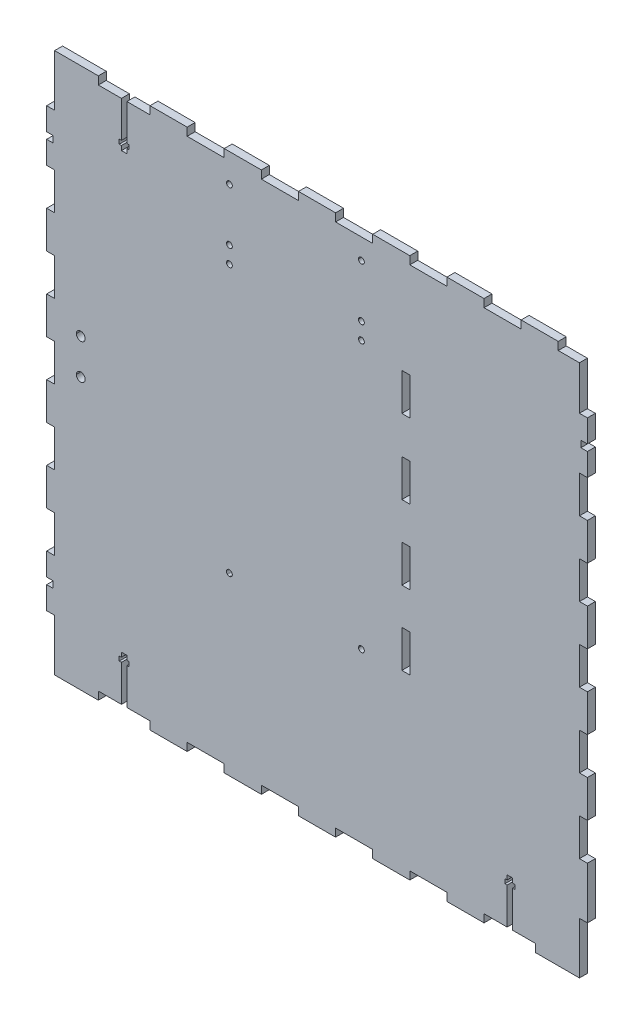
SolidWorks part; units mm, degrees
ref_plane "Front Plane" through (0, 0, 0) normal (0, 0, 1) x (1, 0, 0)
ref_plane "Top Plane" through (0, 0, 0) normal (0, 1, 0) x (1, 0, 0)
ref_plane "Right Plane" through (0, 0, 0) normal (1, 0, 0) x (0, 0, -1)
sketch "Model" plane through (0, 0, 0) normal (0, 0, 1) x (1, 0, 0)
  line L0 (1019.5257, -829.5027) -> (994.7754, -829.5027)
  line L1 (994.7754, -829.5027) -> (994.7754, -825.0027)
  line L2 (994.7754, -825.0027) -> (981.7006, -825.0027)
  line L3 (981.7006, -825.0027) -> (981.7006, -804.4028)
  line L4 (981.7006, -804.4028) -> (982.9505, -804.4028)
  line L5 (982.9505, -804.4028) -> (982.9505, -801.9027)
  line L6 (982.9505, -801.9027) -> (981.7006, -801.9027)
  line L7 (981.7006, -801.9027) -> (981.7006, -799.4025)
  line L8 (981.7006, -799.4025) -> (978.6007, -799.4025)
  line L9 (978.6007, -799.4025) -> (978.6007, -801.9027)
  line L10 (978.6007, -801.9027) -> (977.3505, -801.9027)
  line L11 (977.3505, -801.9027) -> (977.3505, -804.4028)
  line L12 (977.3505, -804.4028) -> (978.6007, -804.4028)
  line L13 (978.6007, -804.4028) -> (978.6007, -825.0027)
  line L14 (978.6007, -825.0027) -> (965.5256, -825.0027)
  line L15 (965.5256, -825.0027) -> (965.5256, -829.5027)
  line L16 (965.5256, -829.5027) -> (944.5256, -829.5027)
  line L17 (944.5256, -829.5027) -> (944.5256, -825.0027)
  line L18 (944.5256, -825.0027) -> (923.5257, -825.0027)
  line L19 (923.5257, -825.0027) -> (923.5257, -829.5027)
  line L20 (923.5257, -829.5027) -> (902.5254, -829.5027)
  line L21 (902.5254, -829.5027) -> (902.5254, -825.0027)
  line L22 (902.5254, -825.0027) -> (881.5255, -825.0027)
  line L23 (881.5255, -825.0027) -> (881.5255, -829.5027)
  line L24 (881.5255, -829.5027) -> (860.5256, -829.5027)
  line L25 (860.5256, -829.5027) -> (860.5256, -825.0027)
  line L26 (860.5256, -825.0027) -> (839.5257, -825.0027)
  line L27 (839.5257, -825.0027) -> (839.5257, -829.5027)
  line L28 (839.5257, -829.5027) -> (818.5258, -829.5027)
  line L29 (818.5258, -829.5027) -> (818.5258, -825.0027)
  line L30 (818.5258, -825.0027) -> (797.5255, -825.0027)
  line L31 (797.5255, -825.0027) -> (797.5255, -829.5027)
  line L32 (797.5255, -829.5027) -> (776.5256, -829.5027)
  line L33 (776.5256, -829.5027) -> (776.5256, -825.0027)
  line L34 (776.5256, -825.0027) -> (763.4507, -825.0027)
  line L35 (763.4507, -825.0027) -> (763.4507, -804.4028)
  line L36 (763.4507, -804.4028) -> (764.7006, -804.4028)
  line L37 (764.7006, -804.4028) -> (764.7006, -801.9027)
  line L38 (764.7006, -801.9027) -> (763.4507, -801.9027)
  line L39 (763.4507, -801.9027) -> (763.4507, -799.4025)
  line L40 (763.4507, -799.4025) -> (760.3505, -799.4025)
  line L41 (760.3505, -799.4025) -> (760.3505, -801.9027)
  line L42 (760.3505, -801.9027) -> (759.1006, -801.9027)
  line L43 (759.1006, -801.9027) -> (759.1006, -804.4028)
  line L44 (759.1006, -804.4028) -> (760.3505, -804.4028)
  line L45 (760.3505, -804.4028) -> (760.3505, -825.0027)
  line L46 (760.3505, -825.0027) -> (747.2757, -825.0027)
  line L47 (747.2757, -825.0027) -> (747.2757, -829.5027)
  line L48 (747.2757, -829.5027) -> (722.5258, -829.5027)
  line L49 (722.5258, -829.5027) -> (722.5258, -800.2528)
  line L50 (722.5258, -800.2528) -> (718.0258, -800.2528)
  line L51 (718.0258, -800.2528) -> (718.0258, -787.4777)
  line L52 (718.0258, -787.4777) -> (721.7258, -787.4777)
  line L53 (721.7258, -787.4777) -> (721.7258, -783.7776)
  line L54 (721.7258, -783.7776) -> (718.0258, -783.7776)
  line L55 (718.0258, -783.7776) -> (718.0258, -771.0025)
  line L56 (718.0258, -771.0025) -> (722.5258, -771.0025)
  line L57 (722.5258, -771.0025) -> (722.5258, -750.0026)
  line L58 (722.5258, -750.0026) -> (718.0258, -750.0026)
  line L59 (718.0258, -750.0026) -> (718.0258, -729.0027)
  line L60 (718.0258, -729.0027) -> (722.5258, -729.0027)
  line L61 (722.5258, -729.0027) -> (722.5258, -708.0028)
  line L62 (722.5258, -708.0028) -> (718.0258, -708.0028)
  line L63 (718.0258, -708.0028) -> (718.0258, -687.0025)
  line L64 (718.0258, -687.0025) -> (722.5258, -687.0025)
  line L65 (722.5258, -687.0025) -> (722.5258, -666.0026)
  line L66 (722.5258, -666.0026) -> (718.0258, -666.0026)
  line L67 (718.0258, -666.0026) -> (718.0258, -645.0027)
  line L68 (718.0258, -645.0027) -> (722.5258, -645.0027)
  line L69 (722.5258, -645.0027) -> (722.5258, -624.0028)
  line L70 (722.5258, -624.0028) -> (718.0258, -624.0028)
  line L71 (718.0258, -624.0028) -> (718.0258, -603.0025)
  line L72 (718.0258, -603.0025) -> (722.5258, -603.0025)
  line L73 (722.5258, -603.0025) -> (722.5258, -582.0025)
  line L74 (722.5258, -582.0025) -> (718.0258, -582.0025)
  line L75 (718.0258, -582.0025) -> (718.0258, -569.2278)
  line L76 (721.7258, -569.2278) -> (718.0258, -569.2278)
  line L77 (721.7258, -569.2278) -> (721.7258, -565.5278)
  line L78 (721.7258, -565.5278) -> (718.0258, -565.5278)
  line L79 (718.0258, -565.5278) -> (718.0258, -552.7526)
  line L80 (718.0258, -552.7526) -> (722.5258, -552.7526)
  line L81 (722.5258, -552.7526) -> (722.5258, -523.5027)
  line L82 (722.5258, -523.5027) -> (747.2757, -523.5027)
  line L83 (747.2757, -523.5027) -> (747.2757, -528.0027)
  line L84 (747.2757, -528.0027) -> (760.3505, -528.0027)
  line L85 (760.3505, -528.0027) -> (760.3505, -548.6027)
  line L86 (760.3505, -548.6027) -> (759.1006, -548.6027)
  line L87 (759.1006, -548.6027) -> (759.1006, -551.1028)
  line L88 (759.1006, -551.1028) -> (760.3505, -551.1028)
  line L89 (760.3505, -551.1028) -> (760.3505, -553.6026)
  line L90 (760.3505, -553.6026) -> (763.4507, -553.6026)
  line L91 (763.4507, -553.6026) -> (763.4507, -551.1028)
  line L92 (763.4507, -551.1028) -> (764.7006, -551.1028)
  line L93 (764.7006, -551.1028) -> (764.7006, -548.6027)
  line L94 (764.7006, -548.6027) -> (763.4507, -548.6027)
  line L95 (763.4507, -548.6027) -> (763.4507, -528.0027)
  line L96 (763.4507, -528.0027) -> (776.5256, -528.0027)
  line L97 (776.5256, -528.0027) -> (776.5256, -523.5027)
  line L98 (776.5256, -523.5027) -> (797.5255, -523.5027)
  line L99 (797.5255, -523.5027) -> (797.5255, -528.0027)
  line L100 (797.5255, -528.0027) -> (818.5258, -528.0027)
  line L101 (818.5258, -528.0027) -> (818.5258, -523.5027)
  line L102 (818.5258, -523.5027) -> (839.5257, -523.5027)
  line L103 (839.5257, -523.5027) -> (839.5257, -528.0027)
  line L104 (839.5257, -528.0027) -> (860.5256, -528.0027)
  line L105 (860.5256, -528.0027) -> (860.5256, -523.5027)
  line L106 (860.5256, -523.5027) -> (881.5255, -523.5027)
  line L107 (881.5255, -523.5027) -> (881.5255, -528.0027)
  line L108 (881.5255, -528.0027) -> (902.5254, -528.0027)
  line L109 (902.5254, -528.0027) -> (902.5254, -523.5027)
  line L110 (902.5254, -523.5027) -> (923.5257, -523.5027)
  line L111 (923.5257, -523.5027) -> (923.5257, -528.0027)
  line L112 (1024.0257, -565.5278) -> (1020.3257, -565.5278)
  line L113 (1020.3257, -565.5278) -> (1020.3257, -569.2278)
  line L114 (1020.3257, -569.2278) -> (1024.0257, -569.2278)
  line L115 (1024.0257, -565.5278) -> (1024.0257, -552.7526)
  line L116 (1024.0257, -552.7526) -> (1019.5257, -552.7526)
  line L117 (1019.5257, -552.7526) -> (1019.5257, -528.0027)
  line L118 (1024.0257, -784.0777) -> (1024.0257, -771.0025)
  line L119 (1024.0257, -771.0025) -> (1019.5257, -771.0025)
  line L120 (1019.5257, -771.0025) -> (1019.5257, -750.0026)
  line L121 (1019.5257, -750.0026) -> (1024.0257, -750.0026)
  line L122 (1024.0257, -750.0026) -> (1024.0257, -729.0027)
  line L123 (1024.0257, -729.0027) -> (1019.5257, -729.0027)
  line L124 (1019.5257, -729.0027) -> (1019.5257, -708.0028)
  line L125 (1019.5257, -708.0028) -> (1024.0257, -708.0028)
  line L126 (1024.0257, -708.0028) -> (1024.0257, -687.0025)
  line L127 (1024.0257, -687.0025) -> (1019.5257, -687.0025)
  line L128 (1019.5257, -687.0025) -> (1019.5257, -666.0026)
  line L129 (1019.5257, -666.0026) -> (1024.0257, -666.0026)
  line L130 (1024.0257, -666.0026) -> (1024.0257, -645.0027)
  line L131 (1024.0257, -645.0027) -> (1019.5257, -645.0027)
  line L132 (1019.5257, -645.0027) -> (1019.5257, -624.0028)
  line L133 (1019.5257, -624.0028) -> (1024.0257, -624.0028)
  line L134 (1024.0257, -624.0028) -> (1024.0257, -603.0028)
  line L135 (1024.0257, -603.0028) -> (1019.5257, -603.0028)
  line L136 (1019.5257, -603.0028) -> (1019.5257, -582.0025)
  line L137 (1019.5257, -582.0025) -> (1024.0257, -582.0025)
  line L138 (1024.0257, -582.0025) -> (1024.0257, -569.2278)
  line L139 (1019.5257, -825.0027) -> (1019.5257, -800.2528)
  line L140 (1019.5257, -800.2528) -> (1024.0257, -800.2528)
  line L141 (1024.0257, -800.2528) -> (1024.0257, -787.1776)
  line L143 (923.5257, -528.0027) -> (944.5256, -528.0027)
  line L146 (919.0257, -603.0693) -> (923.5257, -603.0693)
  line L147 (923.5257, -603.0693) -> (923.5257, -581.9777)
  line L148 (923.5257, -581.9777) -> (919.0257, -581.9777)
  line L149 (919.0257, -581.9777) -> (919.0257, -603.0693)
  line L150 (919.0257, -645.285) -> (923.5257, -645.285)
  line L151 (923.5257, -645.285) -> (923.5257, -624.1934)
  line L152 (923.5257, -624.1934) -> (919.0257, -624.1934)
  line L153 (919.0257, -624.1934) -> (919.0257, -645.285)
  line L154 (919.0257, -687.2206) -> (923.5257, -687.2206)
  line L155 (923.5257, -687.2206) -> (923.5257, -666.129)
  line L156 (923.5257, -666.129) -> (919.0257, -666.129)
  line L157 (919.0257, -666.129) -> (919.0257, -687.2206)
  line L158 (919.0257, -729.0027) -> (923.5257, -729.0027)
  line L159 (923.5257, -729.0027) -> (923.5257, -707.9111)
  line L160 (923.5257, -707.9111) -> (919.0257, -707.9111)
  line L161 (919.0257, -707.9111) -> (919.0257, -729.0027)
  line L162 (1024.0257, -784.0777) -> (1024.0257, -787.1776)
  line L171 (1019.5257, -829.5027) -> (1019.5257, -825.0027)
  line L173 (944.5256, -523.5027) -> (944.5256, -528.0027)
  line L174 (965.5256, -523.5027) -> (944.5256, -523.5027)
  line L175 (965.5256, -528.0027) -> (965.5256, -523.5027)
  line L176 (986.5255, -528.0027) -> (965.5256, -528.0027)
  line L177 (986.5255, -523.5027) -> (986.5255, -528.0027)
  line L178 (1007.5258, -523.5027) -> (986.5255, -523.5027)
  line L179 (1007.5258, -523.5027) -> (1007.5258, -528.0027)
  line L180 (1007.5258, -528.0027) -> (1019.5257, -528.0027)
  spline S0 degree 3 poles (734.826, -676.0807) (734.826, -674.6999) (735.9452, -673.5806) (737.3259, -673.5806) (738.7067, -673.5806) (739.826, -674.6999) (739.826, -676.0807) knots 2 2 2 2 3 3 3 4 4 4 4
  spline S1 degree 3 poles (739.826, -676.0807) (739.826, -677.4613) (738.7067, -678.5806) (737.3259, -678.5806) (735.9452, -678.5806) (734.826, -677.4613) (734.826, -676.0807) knots 0 0 0 0 1 1 1 2 2 2 2
  spline S2 degree 3 poles (734.826, -656.0566) (734.826, -654.6758) (735.9452, -653.5565) (737.3259, -653.5565) (738.7067, -653.5565) (739.826, -654.6758) (739.826, -656.0566) knots 2 2 2 2 3 3 3 4 4 4 4
  spline S3 degree 3 poles (739.826, -656.0566) (739.826, -657.4372) (738.7067, -658.5565) (737.3259, -658.5565) (735.9452, -658.5565) (734.826, -657.4372) (734.826, -656.0566) knots 0 0 0 0 1 1 1 2 2 2 2
  spline S4 degree 3 poles (894.497, -569.2779) (894.497, -568.3667) (895.2356, -567.6281) (896.1472, -567.6281) (897.0581, -567.6281) (897.797, -568.3667) (897.797, -569.2779) knots 2 2 2 2 3 3 3 4 4 4 4
  spline S5 degree 3 poles (897.797, -569.2779) (897.797, -570.1891) (897.0581, -570.9281) (896.1472, -570.9281) (895.2356, -570.9281) (894.497, -570.1891) (894.497, -569.2779) knots 0 0 0 0 1 1 1 2 2 2 2
  spline S6 degree 3 poles (819.797, -569.2779) (819.797, -568.3667) (820.5356, -567.6281) (821.4472, -567.6281) (822.3581, -567.6281) (823.0971, -568.3667) (823.0971, -569.2779) knots 2 2 2 2 3 3 3 4 4 4 4
  spline S7 degree 3 poles (823.0971, -569.2779) (823.0971, -570.1891) (822.3581, -570.9281) (821.4472, -570.9281) (820.5356, -570.9281) (819.797, -570.1891) (819.797, -569.2779) knots 0 0 0 0 1 1 1 2 2 2 2
  spline S8 degree 3 poles (819.797, -539.5777) (819.797, -538.6665) (820.5356, -537.9279) (821.4472, -537.9279) (822.3581, -537.9279) (823.0971, -538.6665) (823.0971, -539.5777) knots 2 2 2 2 3 3 3 4 4 4 4
  spline S9 degree 3 poles (823.0971, -539.5777) (823.0971, -540.489) (822.3581, -541.228) (821.4472, -541.228) (820.5356, -541.228) (819.797, -540.489) (819.797, -539.5777) knots 0 0 0 0 1 1 1 2 2 2 2
  spline S10 degree 3 poles (894.497, -539.5777) (894.497, -538.6665) (895.2356, -537.9279) (896.1472, -537.9279) (897.0581, -537.9279) (897.797, -538.6665) (897.797, -539.5777) knots 2 2 2 2 3 3 3 4 4 4 4
  spline S11 degree 3 poles (897.797, -539.5777) (897.797, -540.489) (897.0581, -541.228) (896.1472, -541.228) (895.2356, -541.228) (894.497, -540.489) (894.497, -539.5777) knots 0 0 0 0 1 1 1 2 2 2 2
  spline S12 degree 3 poles (894.497, -578.7309) (894.497, -577.8197) (895.2356, -577.0811) (896.1472, -577.0811) (897.0581, -577.0811) (897.797, -577.8197) (897.797, -578.7309) knots 2 2 2 2 3 3 3 4 4 4 4
  spline S13 degree 3 poles (897.797, -578.7309) (897.797, -579.6421) (897.0581, -580.3811) (896.1472, -580.3811) (895.2356, -580.3811) (894.497, -579.6421) (894.497, -578.7309) knots 0 0 0 0 1 1 1 2 2 2 2
  spline S14 degree 3 poles (819.797, -578.7309) (819.797, -577.8197) (820.5356, -577.0811) (821.4472, -577.0811) (822.3581, -577.0811) (823.0971, -577.8197) (823.0971, -578.7309) knots 2 2 2 2 3 3 3 4 4 4 4
  spline S15 degree 3 poles (823.0971, -578.7309) (823.0971, -579.6421) (822.3581, -580.3811) (821.4472, -580.3811) (820.5356, -580.3811) (819.797, -579.6421) (819.797, -578.7309) knots 0 0 0 0 1 1 1 2 2 2 2
  spline S16 degree 3 poles (819.797, -730.0609) (819.797, -729.1497) (820.5358, -728.411) (821.4474, -728.411) (822.3582, -728.411) (823.0974, -729.1497) (823.0974, -730.0609) knots 2 2 2 2 3 3 3 4 4 4 4
  spline S17 degree 3 poles (823.0974, -730.0609) (823.0974, -730.9721) (822.3582, -731.7111) (821.4474, -731.7111) (820.5358, -731.7111) (819.797, -730.9721) (819.797, -730.0609) knots 0 0 0 0 1 1 1 2 2 2 2
  spline S18 degree 3 poles (894.497, -730.0609) (894.497, -729.1497) (895.2356, -728.411) (896.1472, -728.411) (897.0581, -728.411) (897.7974, -729.1497) (897.7974, -730.0609) knots 2 2 2 2 3 3 3 4 4 4 4
  spline S19 degree 3 poles (897.7974, -730.0609) (897.7974, -730.9721) (897.0581, -731.7111) (896.1472, -731.7111) (895.2356, -731.7111) (894.497, -730.9721) (894.497, -730.0609) knots 0 0 0 0 1 1 1 2 2 2 2
extrude "Boss-Extrude1" add sketch "Model" along normal blind 4.5
sketch "Sketch1" plane through (0, 0, 4.5) normal (0, 0, 1) x (1, 0, 0)
  circle A0 centre (896.147, -578.7309) radius 1.65
  circle A2 centre (821.4472, -730.0609) radius 1.6502
extrude "Cut-Extrude1" cut sketch "Sketch1" against normal blind 10
sketch "Sketch2" plane through (0, 0, 0) normal (0, 0, -1) x (-1, 0, 0)
  spline S0 degree 3 poles (-2405.4736, -1770.0953) (-742.9358, -508.9748) (-720.3307, -678.5806) (-737.3259, -678.5806) (-754.3238, -678.5806) (-731.692, -508.9635) (930.732, -1770.2209) knots -11.309728 -11.309728 -11.309728 -11.309728 1 1 1 13.310136 13.310136 13.310136 13.310136 only from (-734.826, -676.0807) to (-739.826, -676.0807) construction
  spline S1 degree 3 poles (930.8398, 417.9937) (-731.691, -843.2104) (-754.3242, -673.5806) (-737.3259, -673.5806) (-720.3304, -673.5806) (-742.9367, -843.1984) (-2405.5705, 417.8599) knots -9.310402 -9.310402 -9.310402 -9.310402 3 3 3 15.309967 15.309967 15.309967 15.309967 only from (-739.826, -676.0807) to (-734.826, -676.0807) construction
  spline S2 degree 3 poles (-2405.4736, -1750.0712) (-742.9358, -488.9507) (-720.3307, -658.5565) (-737.3259, -658.5565) (-754.3238, -658.5565) (-731.692, -488.9394) (930.732, -1750.1968) knots -11.309728 -11.309728 -11.309728 -11.309728 1 1 1 13.310136 13.310136 13.310136 13.310136 only from (-734.826, -656.0566) to (-739.826, -656.0566) construction
  spline S3 degree 3 poles (930.9124, 437.8915) (-731.6904, -823.1859) (-754.3244, -653.5565) (-737.3259, -653.5565) (-720.33, -653.5565) (-742.9376, -823.1752) (-2405.663, 437.7728) knots -9.310582 -9.310582 -9.310582 -9.310582 3 3 3 15.310195 15.310195 15.310195 15.310195 only from (-739.826, -656.0566) to (-734.826, -656.0566) construction
  spline S4 degree 3 poles (-734.826, -676.0807) (-734.826, -677.4613) (-735.9452, -678.5806) (-737.3259, -678.5806) (-738.7067, -678.5806) (-739.826, -677.4613) (-739.826, -676.0807) knots 0 0 0 0 1 1 1 2 2 2 2
  spline S5 degree 3 poles (-739.826, -676.0807) (-739.826, -674.6999) (-738.7067, -673.5806) (-737.3259, -673.5806) (-735.9452, -673.5806) (-734.826, -674.6999) (-734.826, -676.0807) knots 2 2 2 2 3 3 3 4 4 4 4
  spline S6 degree 3 poles (-734.826, -656.0566) (-734.826, -657.4372) (-735.9452, -658.5565) (-737.3259, -658.5565) (-738.7067, -658.5565) (-739.826, -657.4372) (-739.826, -656.0566) knots 0 0 0 0 1 1 1 2 2 2 2
  spline S7 degree 3 poles (-739.826, -656.0566) (-739.826, -654.6758) (-738.7067, -653.5565) (-737.3259, -653.5565) (-735.9452, -653.5565) (-734.826, -654.6758) (-734.826, -656.0566) knots 2 2 2 2 3 3 3 4 4 4 4
